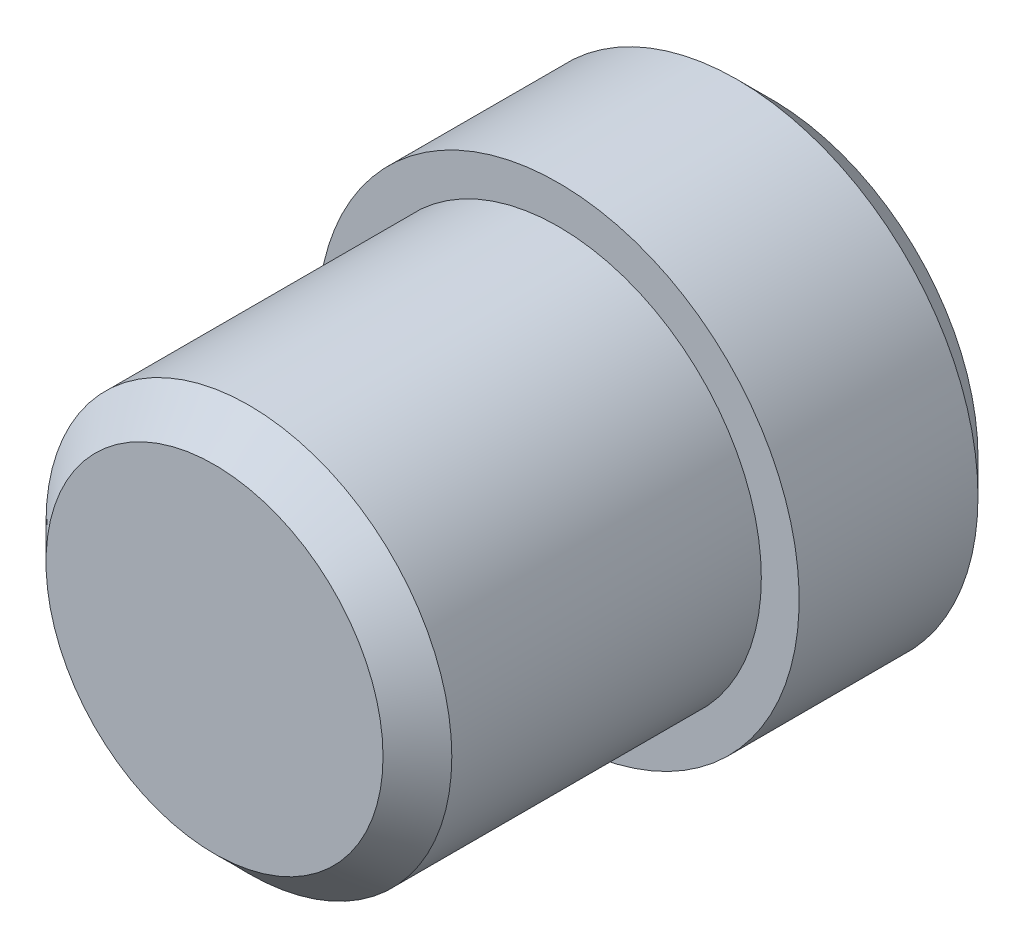
SolidWorks part; units mm, degrees
material "黄铜"
ref_plane "前视基准面" through (0, 0, 0) normal (0, 0, 1) x (1, 0, 0)
ref_plane "上视基准面" through (0, 0, 0) normal (0, 1, 0) x (1, 0, 0)
ref_plane "右视基准面" through (0, 0, 0) normal (1, 0, 0) x (0, 0, -1)
sketch "草图1" plane through (0, 0, 0) normal (0, 0, 1) x (1, 0, 0)
  circle A0 centre (0, 0) radius 3.5
  dimension "D1" = 7
extrude "拉伸1" add sketch "草图1" along normal blind 3.1
sketch "草图2" plane through (0, 0, 3.1) normal (0, 0, 1) x (1, 0, 0)
  circle A0 centre (0, 0) radius 2.95
  dimension "D1" = 5.9
extrude "拉伸2" add sketch "草图2" along normal blind 5
chamfer "倒角1" distance 0.5 angle 45 2 edges at (3.5, 0, 0) (2.95, 0, 8.1)
